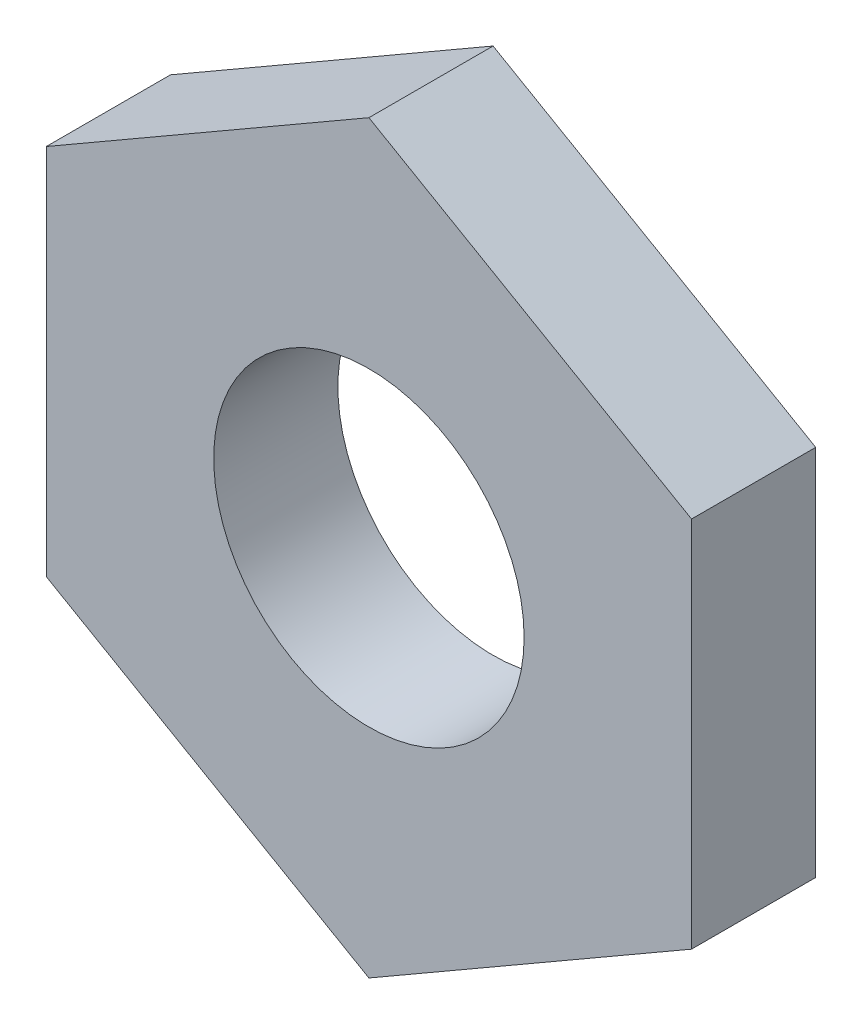
SolidWorks part; units mm, degrees
ref_plane "Plan de face" through (0, 0, 0) normal (0, 0, 1) x (1, 0, 0)
ref_plane "Plan de dessus" through (0, 0, 0) normal (0, 1, 0) x (1, 0, 0)
ref_plane "Plan de droite" through (0, 0, 0) normal (1, 0, 0) x (0, 0, -1)
sketch "Esquisse1" plane through (0, 0, 0) normal (0, 0, 1) x (1, 0, 0)
  line L0 (0, 0) -> (0, 3)
  line L2 (0, 3) -> (-2.5981, 1.5)
  line L3 (-2.5981, 1.5) -> (-2.5981, -1.5)
  line L4 (-2.5981, -1.5) -> (0, -3)
  line L5 (0, -3) -> (2.5981, -1.5)
  line L6 (2.5981, -1.5) -> (2.5981, 1.5)
  line L7 (2.5981, 1.5) -> (0, 3)
  circle A2 centre (0, 0) radius 2.5981 construction
  circle A3 centre (0, 0) radius 1.25
  dimension "D1" = 3
  dimension "D2" = 2.5
extrude "Boss.-Extru.3" add sketch "Esquisse1" along normal blind 1
